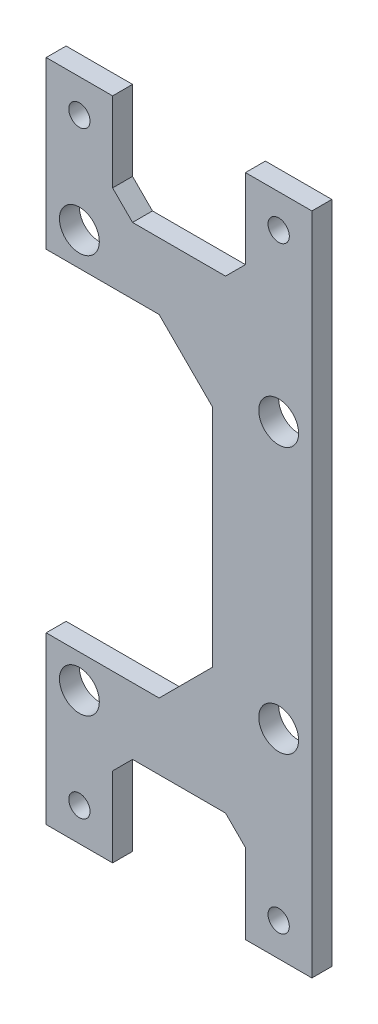
SolidWorks part; units mm, degrees
ref_plane "正面" through (0, 0, 0) normal (0, 0, 1) x (1, 0, 0)
ref_plane "平面" through (0, 0, 0) normal (0, 1, 0) x (1, 0, 0)
ref_plane "右側面" through (0, 0, 0) normal (1, 0, 0) x (0, 0, -1)
sketch "ｽｹｯﾁ1" plane through (0, 0, 0) normal (0, 0, 1) x (1, 0, 0)
  line L1 (0, 0) -> (40, 0)
  line L2 (0, 0) -> (0, 100)
  line L3 (0, 100) -> (40, 100)
  line L4 (40, 0) -> (40, 100)
  circle A0 centre (5, 95) radius 1.6
  circle A1 centre (35, 95) radius 1.6
  circle A2 centre (5, 80) radius 3
  circle A3 centre (35, 70) radius 3
  circle A4 centre (5, 20) radius 3
  circle A5 centre (35, 30) radius 3
  circle A6 centre (5, 5) radius 1.6
  circle A7 centre (35, 5) radius 1.6
  dimension "D3" = 5
  dimension "D4" = 3.2
  dimension "D5" = 5
  dimension "D6" = 15
  dimension "D7" = 5
  dimension "D8" = 6
  dimension "D9" = 6
  dimension "D10" = 5
  dimension "D11" = 25
  dimension "D13" = 5
  dimension "D14" = 3.2
  dimension "D15" = 3.2
  dimension "D16" = 5
  dimension "D17" = 5
  dimension "D18" = 5
  dimension "D19" = 3.2
  dimension "D20" = 5
  dimension "D21" = 5
  dimension "D22" = 25
  dimension "D23" = 6
  dimension "D24" = 5
  dimension "D25" = 6
  dimension "D26" = 5
  dimension "D27" = 15
  dimension "D1" = 100
  dimension "D2" = 40
  dimension "D12" = 5
extrude "ﾎﾞｽ - 押し出し1" add sketch "ｽｹｯﾁ1" along normal blind 3
sketch "ｽｹｯﾁ2" plane through (0, 0, 3) normal (0, 0, 1) x (1, 0, 0)
  line L0 (0, 100) -> (0, 0) construction
  line L1 (10, 100) -> (30, 100)
  line L2 (10, 100) -> (10, 85)
  line L3 (10, 85) -> (30, 85)
  line L4 (30, 100) -> (30, 85)
  line L5 (10, 15) -> (30, 15)
  line L6 (10, 15) -> (10, 0)
  line L7 (10, 0) -> (30, 0)
  line L8 (30, 15) -> (30, 0)
  line L9 (40, 0) -> (40, 100) construction
  line L12 (40, 100) -> (0, 100) construction
  line L13 (0, 0) -> (40, 0) construction
  dimension "D1" = 10
  dimension "D2" = 10
  dimension "D3" = 15
  dimension "D4" = 0
  dimension "D5" = 0
  dimension "D6" = 10
  dimension "D7" = 10
  dimension "D8" = 15
extrude "ｶｯﾄ - 押し出し1" cut sketch "ｽｹｯﾁ2" against normal through all
chamfer "面取り1" distance 3 angle 45 4 edges at (10, 15, 1.5) (30, 15, 1.5) (10, 85, 1.5) (30, 85, 1.5)
sketch "ｽｹｯﾁ3" plane through (0, 0, 0) normal (0, 0, -1) x (-1, 0, 0)
  line L0 (-40, 100) -> (-30, 100) construction
  line L1 (-25, 75) -> (0, 75)
  line L2 (-25, 75) -> (-25, 25)
  line L3 (-25, 25) -> (0, 25)
  line L4 (0, 75) -> (0, 25)
  line L5 (-30, 0) -> (-40, 0) construction
  line L6 (0, 100) -> (0, 0) construction
  line L7 (-40, 0) -> (-40, 100) construction
  dimension "D1" = 25
  dimension "D2" = 25
  dimension "D3" = 0
  dimension "D4" = 15
extrude "ｶｯﾄ - 押し出し2" cut sketch "ｽｹｯﾁ3" against normal through all
chamfer "面取り2" distance 8 angle 45 2 edges at (25, 25, 1.5) (25, 75, 1.5)
